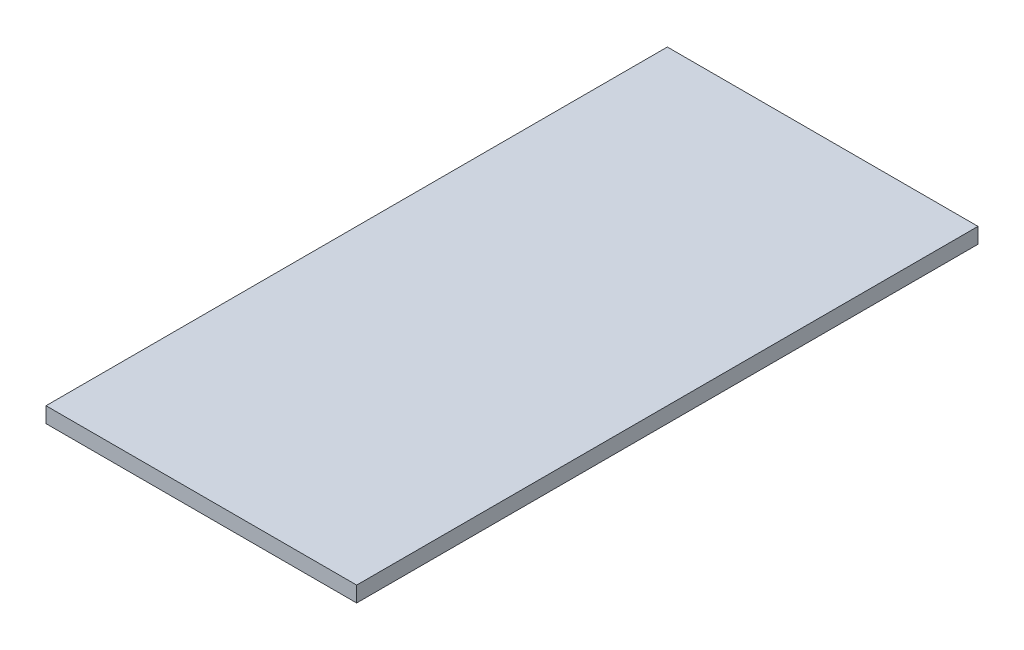
SolidWorks part; units mm, degrees
ref_plane "Front Plane" through (0, 0, 0) normal (0, 0, 1) x (1, 0, 0)
ref_plane "Top Plane" through (0, 0, 0) normal (0, 1, 0) x (1, 0, 0)
ref_plane "Right Plane" through (0, 0, 0) normal (1, 0, 0) x (0, 0, -1)
sketch "Sketch1" plane through (0, 0, 0) normal (0, 1, 0) x (1, 0, 0)
  line L1 (-50, 100) -> (50, 100)
  line L2 (-50, 100) -> (-50, -100)
  line L3 (-50, -100) -> (50, -100)
  line L4 (50, 100) -> (50, -100)
  line L5 (-50, 100) -> (50, -100) construction
  line L6 (-50, -100) -> (50, 100) construction
  point P0 (0, 0)
  dimension "D1" = 200
  dimension "D2" = 100
extrude "Boss-Extrude2" add sketch "Sketch1" along normal blind 5
